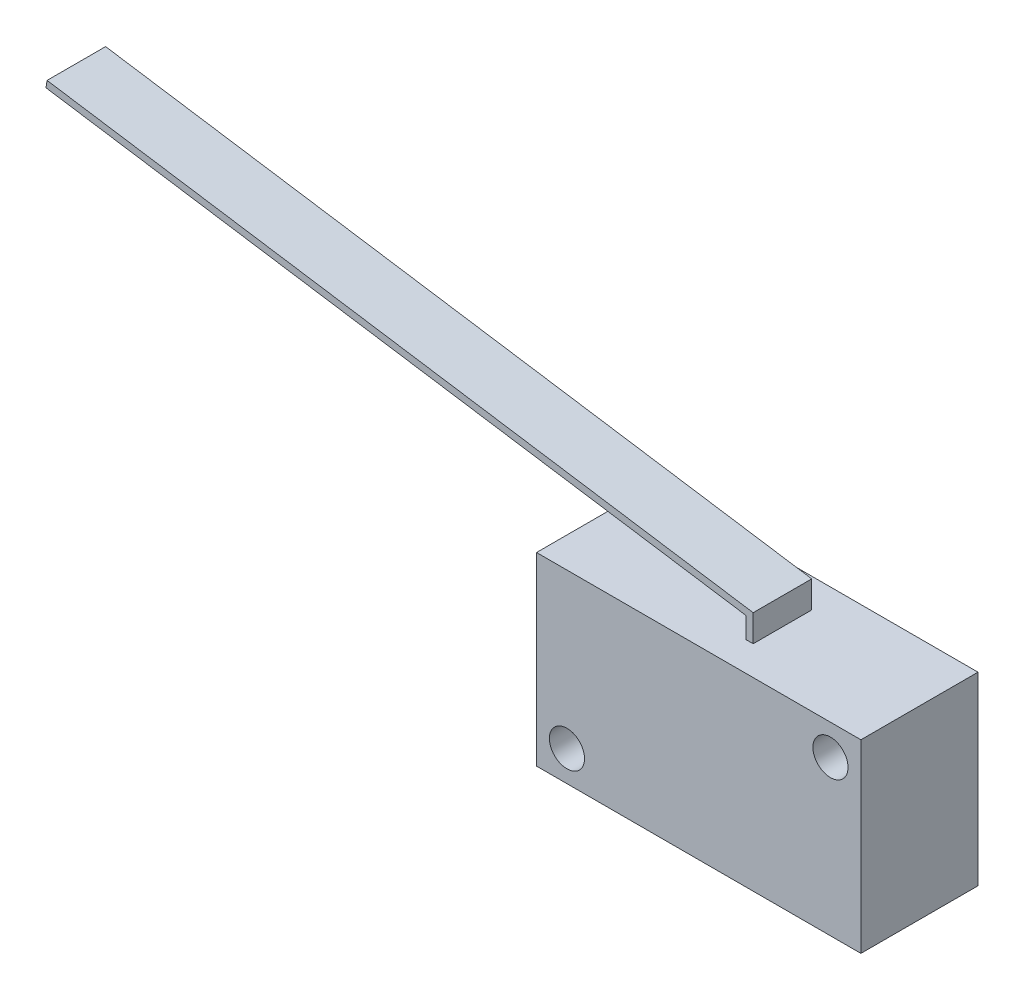
SolidWorks part; units mm, degrees
ref_plane "正面" through (0, 0, 0) normal (0, 0, 1) x (1, 0, 0)
ref_plane "平面" through (0, 0, 0) normal (0, 1, 0) x (1, 0, 0)
ref_plane "右側面" through (0, 0, 0) normal (1, 0, 0) x (0, 0, -1)
sketch "ｽｹｯﾁ1" plane through (0, 0, 0) normal (0, 0, 1) x (1, 0, 0)
  line L1 (13.85, -7.9) -> (-13.85, -7.9)
  line L2 (13.85, -7.9) -> (13.85, 7.9)
  line L3 (13.85, 7.9) -> (-13.85, 7.9)
  line L4 (-13.85, -7.9) -> (-13.85, 7.9)
  line L5 (13.85, -7.9) -> (-13.85, 7.9) construction
  line L6 (13.85, 7.9) -> (-13.85, -7.9) construction
  line L7 (11.25, -5.3) -> (-11.25, -5.3) construction
  line L8 (11.25, -5.3) -> (11.25, 5.3) construction
  line L9 (11.25, 5.3) -> (-11.25, 5.3) construction
  line L10 (-11.25, -5.3) -> (-11.25, 5.3) construction
  line L11 (11.25, -5.3) -> (-11.25, 5.3) construction
  line L12 (11.25, 5.3) -> (-11.25, -5.3) construction
  circle A0 centre (11.25, 5.3) radius 1.5
  circle A1 centre (-11.25, -5.3) radius 1.5
  point P0 (0, 0)
  point P10 (0, 0)
  dimension "D3" = 22.5
  dimension "D5" = 3
  dimension "D1" = 27.7
  dimension "D2" = 15.8
  dimension "D4" = 10.6
extrude "ﾎﾞｽ - 押し出し1" add sketch "ｽｹｯﾁ1" along normal mid plane 10
sketch "ｽｹｯﾁ2" plane through (0, 0, 0) normal (0, 0, 1) x (1, 0, 0)
  line L0 (2.15, 7.9) -> (2.15, 10.2)
  line L1 (13.85, 7.9) -> (-13.85, 7.9) construction
  line L2 (2.15, 10.2) -> (-58.15, 19.4147)
  line L3 (13.85, -7.9) -> (13.85, 7.9) construction
  dimension "D1" = 98.688
  dimension "D2" = 2.3
  dimension "D3" = 11.7
  dimension "D4" = 72
extrude "押し出し-薄板1" add sketch "ｽｹｯﾁ2" along normal mid plane 5 thin thin type one direction reverse wall 0.6
